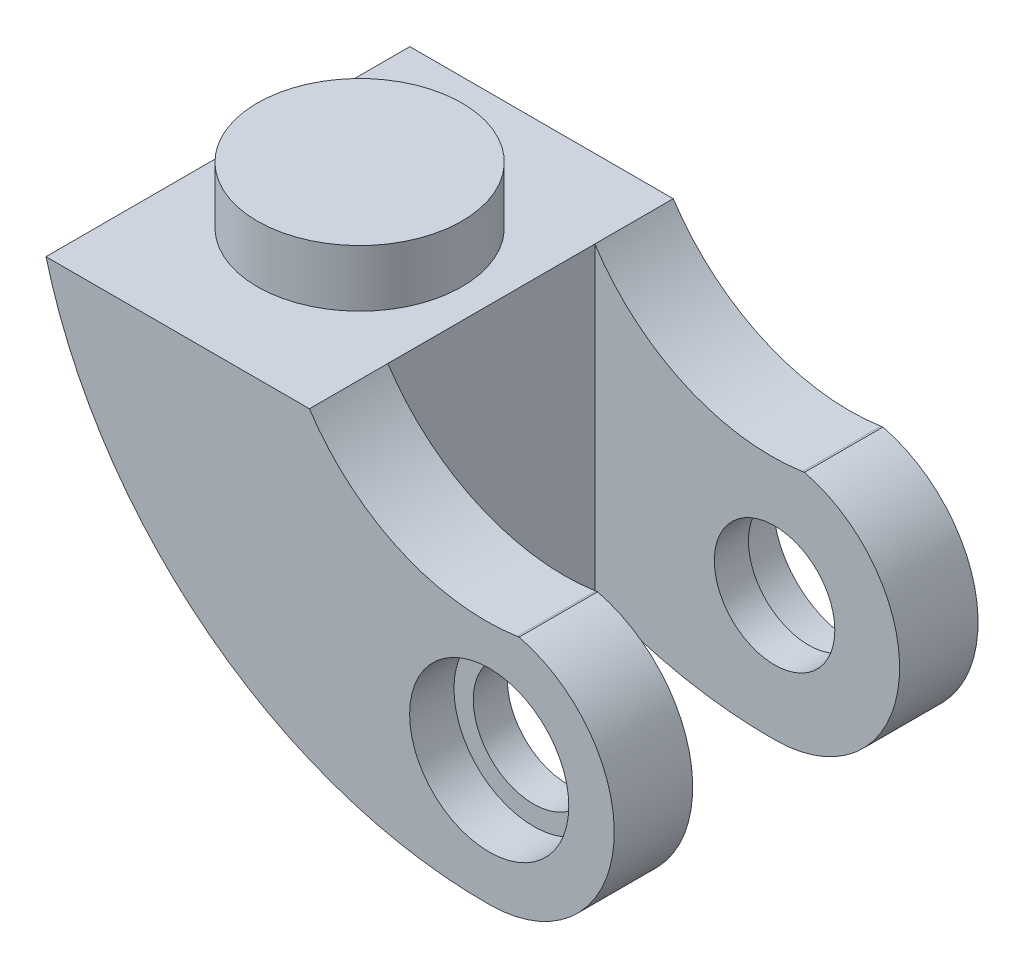
SolidWorks part; units mm, degrees
ref_plane "Alzado" through (0, 0, 0) normal (0, 0, 1) x (1, 0, 0)
ref_plane "Planta" through (0, 0, 0) normal (0, 1, 0) x (1, 0, 0)
ref_plane "Vista lateral" through (0, 0, 0) normal (1, 0, 0) x (0, 0, -1)
sketch "Croquis1" plane through (0, 0, 0) normal (0, 0, 1) x (1, 0, 0)
  line L0 (-19.4907, 9.4283) -> (-7.9057, 9.4283)
  line L1 (1.2302, 5.3305) -> (1.3144, 5.3406)
  circle A0 centre (0, 0) radius 3.5
  arc A1 (0.0547, -5.4997) -> (1.3144, 5.3406) centre (0, 0) ccw
  arc A2 (-19.4907, 9.4283) -> (0.0547, -5.4997) centre (-0.1443, 14.4993) ccw
  arc A5 (-7.9057, 9.4283) -> (1.2302, 5.3305) centre (-0.1443, 14.4993) ccw
extrude "Saliente-Extruir1" add sketch "Croquis1" along normal blind 16 contours A0 | A1 L1 A5 L0 A2
sketch "Croquis2" plane through (0, 9.4283, 0) normal (0, 1, 0) x (1, 0, 0)
  line L1 (-7.9057, -16) -> (-7.9057, 0) construction
  line L2 (-7.9057, -12.55) -> (10.327, -12.55)
  line L3 (10.327, -12.55) -> (10.327, -3.45)
  line L5 (-7.9057, -3.45) -> (10.327, -3.45)
  line L6 (-7.9057, -12.55) -> (-7.9057, -3.45)
extrude "Cortar-Extruir1" cut sketch "Croquis2" against normal blind 22
sketch "Croquis3" plane through (0, 0, 12.55) normal (0, 0, -1) x (-1, 0, 0)
  circle A0 centre (0, 0) radius 3.5
  circle A1 centre (0, 0) radius 2.65
extrude "Saliente-Extruir2" add sketch "Croquis3" against normal blind 1.5
sketch "Croquis4" plane through (0, 0, 3.45) normal (0, 0, 1) x (1, 0, 0)
  circle A0 centre (0, 0) radius 3.5
  circle A1 centre (0, 0) radius 2.65
extrude "Saliente-Extruir3" add sketch "Croquis4" against normal blind 1.5
sketch "Croquis5" plane through (0, 9.4283, 0) normal (0, 1, 0) x (1, 0, 0)
  circle A0 centre (-13.6982, -8) radius 4.5
extrude "Saliente-Extruir4" add sketch "Croquis5" along normal blind 2.5
